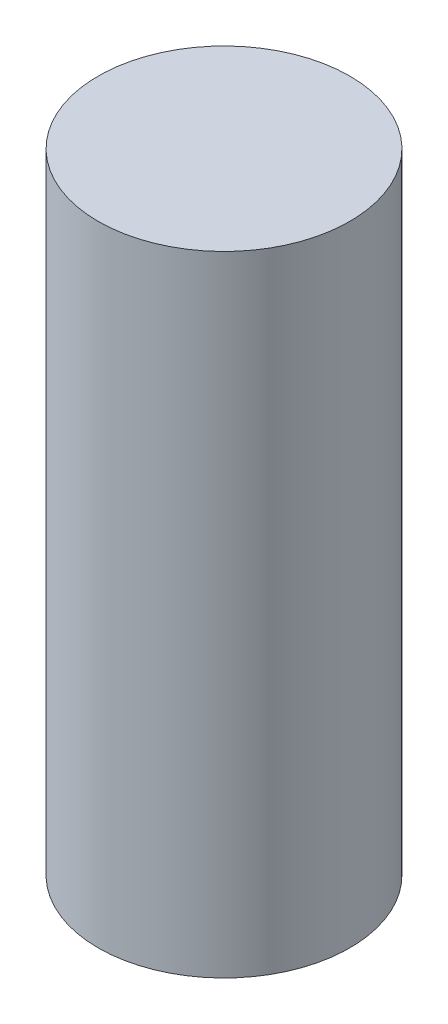
SolidWorks part; units mm, degrees
ref_plane "Front Plane" through (0, 0, 0) normal (0, 0, 1) x (1, 0, 0)
ref_plane "Top Plane" through (0, 0, 0) normal (0, 1, 0) x (1, 0, 0)
ref_plane "Right Plane" through (0, 0, 0) normal (1, 0, 0) x (0, 0, -1)
sketch "Sketch2" plane through (0, 0, 0) normal (0, 1, 0) x (1, 0, 0)
  circle A0 centre (0, 0) radius 20
  dimension "D1" = 40
extrude "Boss-Extrude1" add sketch "Sketch2" along normal blind 100
